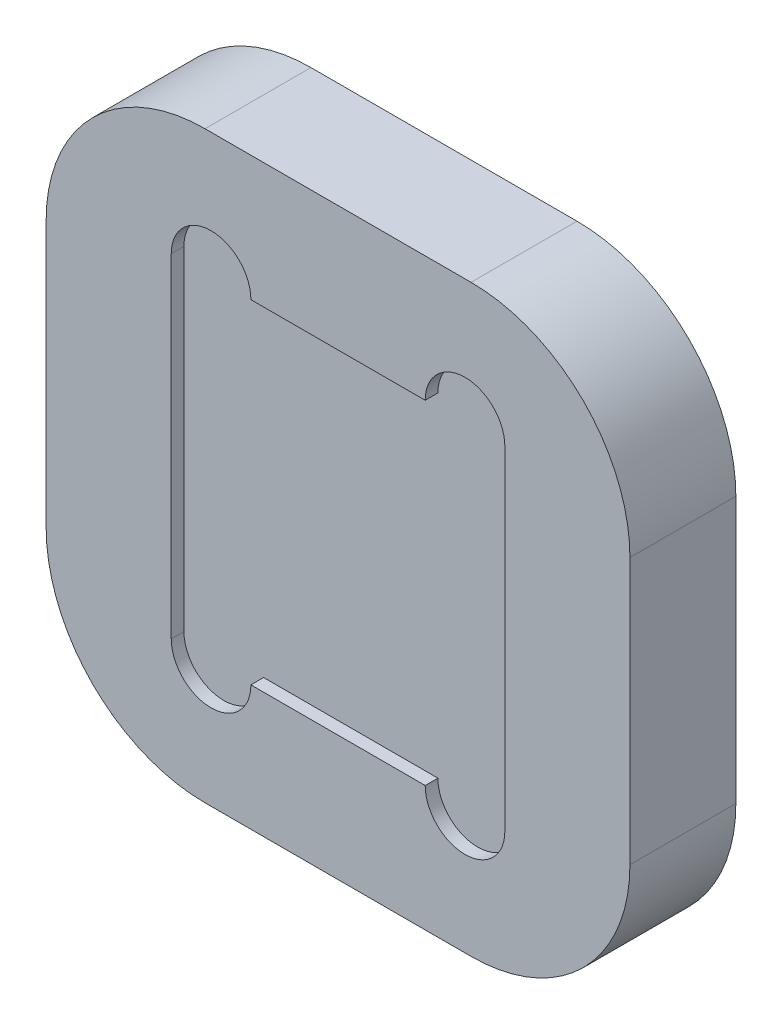
SolidWorks part; units mm, degrees
material "2024 Alloy"
ref_plane "Front Plane" through (0, 0, 0) normal (0, 0, 1) x (1, 0, 0)
ref_plane "Top Plane" through (0, 0, 0) normal (0, 1, 0) x (1, 0, 0)
ref_plane "Right Plane" through (0, 0, 0) normal (1, 0, 0) x (0, 0, -1)
sketch "Sketch1" plane through (0, 0, 0) normal (0, 0, 1) x (1, 0, 0)
  line L1 (-17.5, 17.5) -> (17.5, 17.5)
  line L2 (-17.5, 17.5) -> (-17.5, -17.5)
  line L3 (-17.5, -17.5) -> (17.5, -17.5)
  line L4 (17.5, 17.5) -> (17.5, -17.5)
  line L5 (-17.5, 17.5) -> (17.5, -17.5) construction
  line L6 (-17.5, -17.5) -> (17.5, 17.5) construction
  point P0 (0, 0)
  dimension "D1" = 35
extrude "Boss-Extrude1" add sketch "Sketch1" along normal blind 6.35
sketch "Sketch2" plane through (0, 0, 6.35) normal (0, 0, 1) x (1, 0, 0)
  line L1 (-10, 10) -> (10, 10)
  line L2 (-10, 10) -> (-10, -10)
  line L3 (-10, -10) -> (10, -10)
  line L4 (10, 10) -> (10, -10)
  line L5 (-10, 10) -> (10, -10) construction
  line L6 (-10, -10) -> (10, 10) construction
  point P0 (0, 0)
sketch "Sketch3" plane through (0, 0, 6.35) normal (0, 0, 1) x (1, 0, 0)
  line L0 (-10, 10) -> (-10, -10) construction
  line L1 (-10, -10) -> (10, -10) construction
  line L2 (10, 10) -> (10, -10) construction
  line L3 (-10, 10) -> (10, 10) construction
  line L4 (-10, 10) -> (-10, -10)
  line L5 (-5.2248, -10) -> (5.2248, -10)
  line L6 (10, 10) -> (10, -10)
  line L7 (-5.2248, 10) -> (5.2248, 10)
  arc A0 (-5.2248, 10) -> (-10, 10) centre (-7.6124, 10) ccw
  arc A1 (10, 10) -> (5.2248, 10) centre (7.6124, 10) ccw
  arc A2 (5.2248, -10) -> (10, -10) centre (7.6124, -10) ccw
  arc A3 (-10, -10) -> (-5.2248, -10) centre (-7.6124, -10) ccw
  point P6 (-10, 10)
  point P7 (-5.2248, 10)
  point P10 (5.2248, 10)
  point P11 (10, 10)
  point P14 (-10, -10)
  point P15 (-5.2248, -10)
  point P18 (5.2248, -10)
  point P19 (10, -10)
  dimension "D1" = 4.7752
extrude "Cut-Extrude1" cut sketch "Sketch3" against normal blind 0.762
fillet "Fillet1" radius 9.525 4 edges at (17.5, 17.5, 3.175) (17.5, -17.5, 3.175) (-17.5, 17.5, 3.175) (-17.5, -17.5, 3.175)
sketch "Sketch4" plane through (0, 0, 0) normal (0, 0, -1) x (-1, 0, 0)
  circle A0 centre (0, 0) radius 21.209
  dimension "D1" = 42.418
sketch "Sketch5" plane through (0, 0, 0) normal (0, 0, -1) x (-1, 0, 0)
  line L1 (-15, 15) -> (15, 15)
  line L2 (-15, 15) -> (-15, -15)
  line L3 (-15, -15) -> (15, -15)
  line L4 (15, 15) -> (15, -15)
  line L5 (-15, 15) -> (15, -15) construction
  line L6 (-15, -15) -> (15, 15) construction
  point P0 (0, 0)
  dimension "D1" = 30
